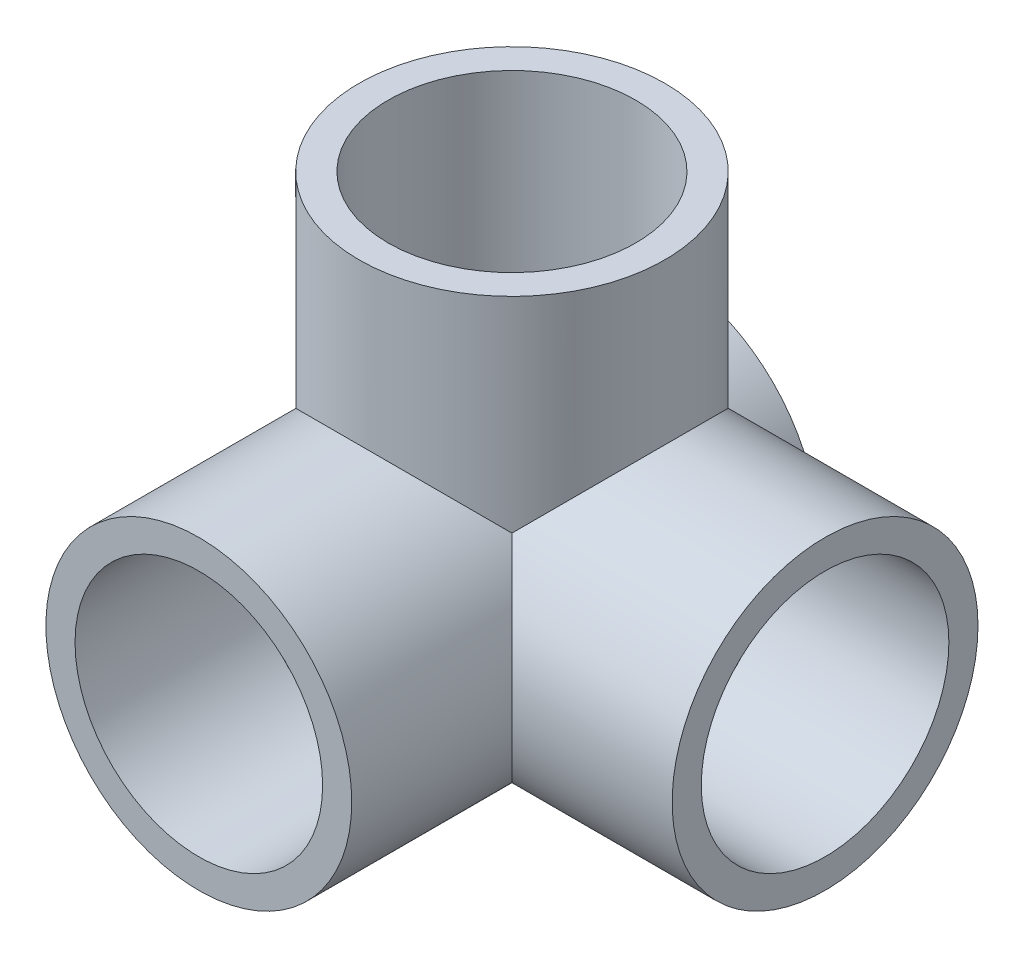
SolidWorks part; units mm, degrees
ref_plane "Front Plane" through (0, 0, 0) normal (0, 0, 1) x (1, 0, 0)
ref_plane "Top Plane" through (0, 0, 0) normal (0, 1, 0) x (1, 0, 0)
ref_plane "Right Plane" through (0, 0, 0) normal (1, 0, 0) x (0, 0, -1)
sketch "Sketch1" plane through (0, 0, 0) normal (0, 0, 1) x (1, 0, 0)
  circle A0 centre (0, 0) radius 16.6687
  dimension "D1" = 33.3375
extrude "Boss-Extrude1" add sketch "Sketch1" along normal blind 50.8
sketch "Sketch2" plane through (0, 0, 0) normal (1, 0, 0) x (0, 0, -1)
  line L0 (0, -16.6687) -> (0, 16.6687) construction
  circle A0 centre (-16.6687, 0) radius 16.6687
  dimension "D1" = 33.3375
  dimension "D2" = 16.6687
extrude "Boss-Extrude2" add sketch "Sketch2" along normal blind 34.1313
sketch "Sketch3" plane through (0, 0, 0) normal (0, 1, 0) x (1, 0, 0)
  line L0 (16.6687, 0) -> (0, -16.6687) construction
  line L1 (16.6687, -33.3375) -> (0, -16.6687) construction
  circle A0 centre (0, -16.6688) radius 16.6687
  dimension "D1" = 33.3375
extrude "Boss-Extrude3" add sketch "Sketch3" along normal blind 34.1313
sketch "Sketch4" plane through (0, 0, 0) normal (0, 1, 0) x (1, 0, 0)
  line L0 (-16.6687, -16.6688) -> (-16.6687, 0)
  line L1 (-16.6687, 0) -> (0, 0)
  arc A0 (-16.6687, -16.6688) -> (0, 0) centre (0, -16.6688) cw
extrude "Cut-Extrude1" cut sketch "Sketch4" against normal through all both and the other way through all
sketch "Sketch5" plane through (34.1313, 0, 0) normal (1, 0, 0) x (0, 0, -1)
  line L0 (-16.6687, -16.6687) -> (0, -16.6687)
  line L1 (0, -16.6687) -> (0, 0)
  arc A0 (0, 0) -> (-16.6687, -16.6687) centre (-16.6687, 0) cw
extrude "Cut-Extrude2" cut sketch "Sketch5" against normal through all
sketch "Sketch8" plane through (0, 34.1313, 0) normal (0, 1, 0) x (1, 0, 0)
  circle A0 centre (0, -16.6688) radius 12.7
extrude "Cut-Extrude3" cut sketch "Sketch8" against normal blind 44.45
sketch "Sketch9" plane through (0, 34.1313, 0) normal (0, 1, 0) x (1, 0, 0)
  circle A0 centre (0, -16.6688) radius 13.4938
  dimension "D1" = 26.9875
extrude "Cut-Extrude4" cut sketch "Sketch9" against normal blind 19.05
sketch "Sketch10" plane through (34.1313, 0, 0) normal (1, 0, 0) x (0, 0, -1)
  circle A0 centre (-16.6687, 0) radius 12.7
extrude "Cut-Extrude5" cut sketch "Sketch10" against normal blind 44.45
sketch "Sketch11" plane through (34.1313, 0, 0) normal (1, 0, 0) x (0, 0, -1)
  circle A0 centre (-16.6688, 0) radius 13.4937
  dimension "D1" = 26.9875
extrude "Cut-Extrude6" cut sketch "Sketch11" against normal blind 19.05
sketch "Sketch12" plane through (0, 0, 50.8) normal (0, 0, 1) x (1, 0, 0)
  circle A0 centre (0, 0) radius 12.7
extrude "Cut-Extrude7" cut sketch "Sketch12" against normal blind 44.45
sketch "Sketch13" plane through (0, 0, 50.8) normal (0, 0, 1) x (1, 0, 0)
  circle A0 centre (0, 0) radius 13.4938
  dimension "D1" = 26.9875
extrude "Cut-Extrude8" cut sketch "Sketch13" against normal blind 19.05
